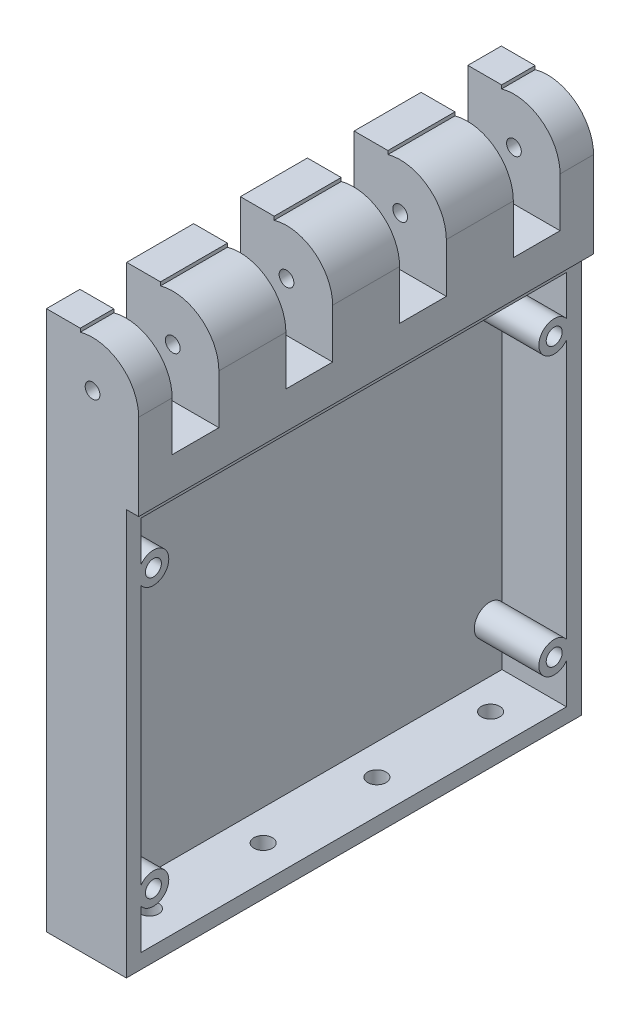
SolidWorks part; units mm, degrees
ref_plane "Front Plane" through (0, 0, 0) normal (0, 0, 1) x (1, 0, 0)
ref_plane "Top Plane" through (0, 0, 0) normal (0, 1, 0) x (1, 0, 0)
ref_plane "Right Plane" through (0, 0, 0) normal (1, 0, 0) x (0, 0, -1)
sketch "Sketch1" plane through (0, 0, 0) normal (0, 0, 1) x (1, 0, 0)
  line L2 (7.5, 0) -> (7.5, -80)
  line L3 (7.5, -80) -> (-7.5, -80)
  line L4 (-7.5, 0) -> (-7.5, -80)
  arc A0 (7.5, 0) -> (-7.5, 0) centre (0, 0) ccw
  dimension "D4" = 15
  dimension "D1" = 15
  dimension "D2" = 7.5
  dimension "D3" = 80
extrude "Boss-Extrude1" add sketch "Sketch1" along normal mid plane 74
sketch "Sketch2" plane through (0, 0, 0) normal (0, 0, 1) x (1, 0, 0)
  line L1 (-7.5, 0) -> (-2, 0)
  line L2 (-7.5, 0) -> (-7.5, 7.8)
  line L3 (-7.5, 7.8) -> (-2, 7.8)
  line L4 (-2, 0) -> (-2, 7.8)
  dimension "D1" = 2
  dimension "D2" = 7.8
extrude "Boss-Extrude2" add sketch "Sketch2" along normal mid plane 74
sketch "Sketch3" plane through (0, 0, 0) normal (1, 0, 0) x (0, 0, -1)
  line L0 (0, 8.25) -> (0, -8.25) construction
  line L1 (-5.45, -8) -> (-13.05, -8)
  line L2 (-5.45, -8) -> (-5.45, 9)
  line L3 (-5.45, 9) -> (-13.05, 9)
  line L4 (-13.05, -8) -> (-13.05, 9)
  line L5 (-23.95, -8) -> (-31.55, -8)
  line L6 (-23.95, -8) -> (-23.95, 9)
  line L7 (-23.95, 9) -> (-31.55, 9)
  line L8 (-31.55, -8) -> (-31.55, 9)
  line L9 (31.55, -8) -> (31.55, 9)
  line L10 (23.95, 9) -> (31.55, 9)
  line L11 (23.95, -8) -> (23.95, 9)
  line L12 (23.95, -8) -> (31.55, -8)
  line L13 (13.05, -8) -> (13.05, 9)
  line L14 (5.45, 9) -> (13.05, 9)
  line L15 (5.45, -8) -> (5.45, 9)
  line L16 (5.45, -8) -> (13.05, -8)
  dimension "D1" = 5.45
  dimension "D2" = 13.05
  dimension "D3" = 8
  dimension "D4" = 9
  dimension "D5" = 23.95
  dimension "D6" = 31.55
  dimension "D7" = 9
  dimension "D8" = 8
extrude "Cut-Extrude1" cut sketch "Sketch3" against normal through all both and the other way through all
sketch "Sketch4" plane through (0, 0, 0) normal (0, 0, 1) x (1, 0, 0)
  circle A0 centre (0, 0) radius 1.2
  dimension "D1" = 2.4
extrude "Cut-Extrude2" cut sketch "Sketch4" against normal through all both and the other way through all
sketch "Sketch5" plane through (0, 0, 0) normal (0, 0, 1) x (1, 0, 0)
  line L1 (5.5, -81) -> (8, -81)
  line L2 (5.5, -81) -> (5.5, -14)
  line L3 (5.5, -14) -> (8, -14)
  line L4 (8, -81) -> (8, -14)
  line L6 (0, -40.7) -> (0, 40.7) construction
  line L7 (8.25, 0) -> (-8.25, 0) construction
  point P10 (0, 0)
  dimension "D1" = 5.5
  dimension "D2" = 81
  dimension "D3" = 2.5
  dimension "D4" = 14
extrude "Cut-Extrude3" cut sketch "Sketch5" against normal through all both and the other way through all
sketch "Sketch6" plane through (5.5, 0, 0) normal (1, 0, 0) x (0, 0, -1)
  line L0 (-37, -14) -> (-37, -80) construction
  line L1 (-34.6, -77.6) -> (34.6, -77.6)
  line L2 (-34.6, -77.6) -> (-34.6, -16.4)
  line L3 (-34.6, -16.4) -> (34.6, -16.4)
  line L4 (34.6, -77.6) -> (34.6, -16.4)
  line L5 (37, -14) -> (37, -80) construction
  line L6 (37, -80) -> (-37, -80) construction
  line L7 (-37, -14) -> (37, -14) construction
  dimension "D1" = 2.4
  dimension "D2" = 2.4
  dimension "D3" = 2.4
  dimension "D4" = 2.4
extrude "Cut-Extrude4" cut sketch "Sketch6" against normal blind 10.5 and the other way through all
sketch "Sketch7" plane through (-5, 0, 0) normal (1, 0, 0) x (0, 0, -1)
  line L1 (-34.6, -16.4) -> (-34.6, -77.6) construction
  line L2 (-34.6, -77.6) -> (34.6, -77.6) construction
  line L3 (34.6, -16.4) -> (-34.6, -16.4) construction
  line L4 (-34.6, -16.4) -> (-34.6, -77.6) construction
  line L5 (34.6, -77.6) -> (34.6, -16.4) construction
  line L6 (34.6, -16.4) -> (-34.6, -16.4) construction
  circle A0 centre (-32.6, -69.6) radius 2.5
  circle A1 centre (-32.6, -24.4) radius 2.5
  circle A2 centre (32.6, -24.4) radius 2.5
  circle A3 centre (32.6, -69.6) radius 2.5
  point P8 (0, 0)
  point P21 (0, 0)
  point P22 (0, 0)
  point P23 (0, 0)
  point P24 (0, 0)
  point P25 (0, 0)
  point P26 (0, 0)
  dimension "D1" = 5
  dimension "D2" = 5
  dimension "D3" = 5
  dimension "D4" = 5
  dimension "D5" = 2
  dimension "D9" = 2
  dimension "D10" = 8
  dimension "D11" = 2
  dimension "D12" = 8
  dimension "D6" = 8
  dimension "D7" = 8
  dimension "D8" = 2
extrude "Boss-Extrude8" add sketch "Sketch7" along normal blind 10.5
sketch "Sketch8" plane through (5.5, 0, 0) normal (1, 0, 0) x (0, 0, -1)
  circle A0 centre (-32.6, -24.4) radius 1.3
  circle A1 centre (32.6, -24.4) radius 1.3
  circle A2 centre (32.6, -69.6) radius 1.3
  circle A3 centre (-32.6, -69.6) radius 1.3
  dimension "D1" = 2.6
  dimension "D2" = 2.6
  dimension "D3" = 2.6
  dimension "D4" = 2.6
extrude "Cut-Extrude5" cut sketch "Sketch8" against normal blind 8
sketch "Sketch9" plane through (0, -80, 0) normal (0, -1, 0) x (1, 0, 0)
  circle A0 centre (0, -9.25) radius 1.5
  circle A1 centre (0, -27.75) radius 1.5
  circle A2 centre (0, 9.25) radius 1.5
  circle A3 centre (0, 27.75) radius 1.5
  point P8 (0, 0)
  point P10 (0, 0)
  point P11 (0.8026, -1.5742)
  dimension "D1" = 3
  dimension "D2" = 3
  dimension "D3" = 3
  dimension "D4" = 3
  dimension "D5" = 27.75
  dimension "D6" = 9.25
  dimension "D7" = 9.25
  dimension "D8" = 27.75
extrude "Cut-Extrude6" cut sketch "Sketch9" against normal blind 3
